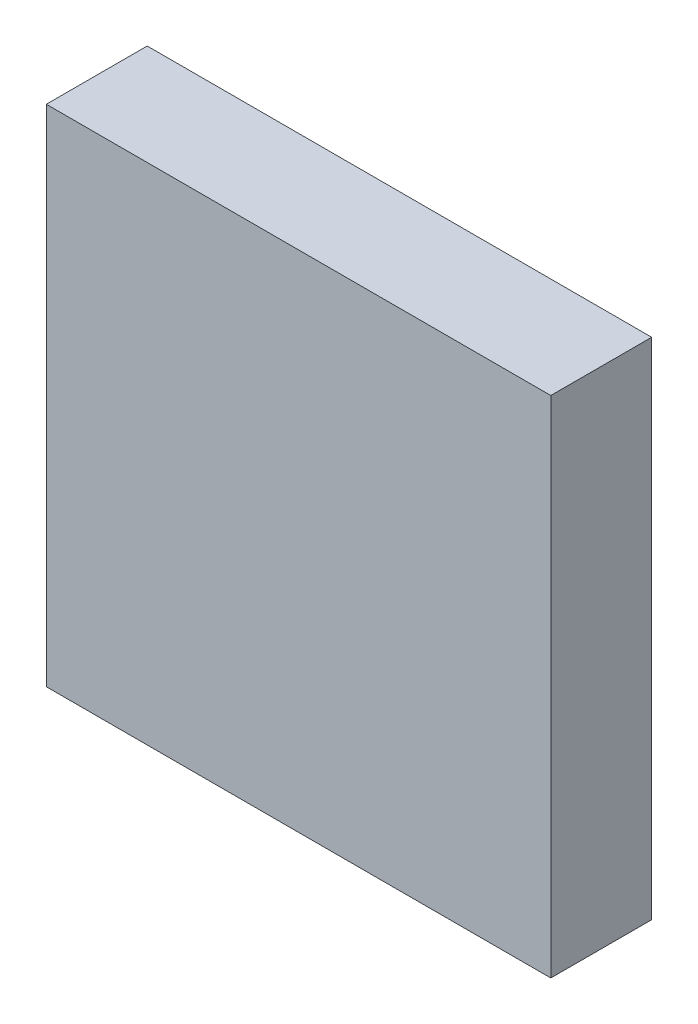
SolidWorks part; units mm, degrees
ref_plane "Front Plane" through (0, 0, 0) normal (0, 0, 1) x (1, 0, 0)
ref_plane "Top Plane" through (0, 0, 0) normal (0, 1, 0) x (1, 0, 0)
ref_plane "Right Plane" through (0, 0, 0) normal (1, 0, 0) x (0, 0, -1)
sketch "Sketch1" plane through (0, 0, 0) normal (0, 0, 1) x (1, 0, 0)
  line L1 (0, 0) -> (25, 0)
  line L2 (0, 0) -> (0, 25)
  line L3 (0, 25) -> (25, 25)
  line L4 (25, 0) -> (25, 25)
  dimension "D1" = 25
extrude "Boss-Extrude1" add sketch "Sketch1" along normal blind 5
